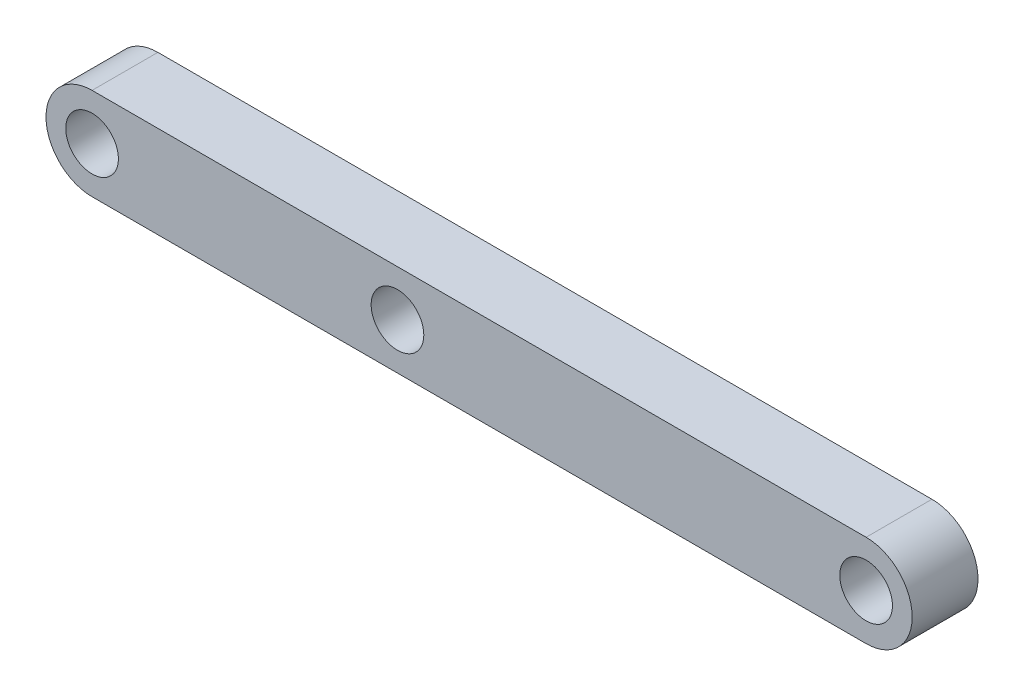
SolidWorks part; units mm, degrees
ref_plane "前视基准面" through (0, 0, 0) normal (0, 0, 1) x (1, 0, 0)
ref_plane "上视基准面" through (0, 0, 0) normal (0, 1, 0) x (1, 0, 0)
ref_plane "右视基准面" through (0, 0, 0) normal (1, 0, 0) x (0, 0, -1)
other "Configuration Table"
sketch "草图1" plane through (0, 0, 0) normal (0, 0, 1) x (1, 0, 0)
  line L0 (0, 0) -> (232, 0)
  line L1 (0, 35) -> (588, 35)
  line L2 (0, -35) -> (588, -35)
  line L3 (232, 0) -> (588, 0)
  arc A0 (588, -35) -> (588, 35) centre (588, 0) ccw
  arc A2 (0, 35) -> (0, -35) centre (0, 0) ccw
  circle A3 centre (0, 0) radius 20
  circle A4 centre (232, 0) radius 20
  circle A5 centre (588, 0) radius 20
  dimension "D1" = 35
  dimension "D2" = 356
  dimension "D4" = 40
  dimension "D5" = 40
  dimension "D6" = 40
  dimension "D3" = 232
extrude "凸台-拉伸1" add sketch "草图1" along normal blind 50
